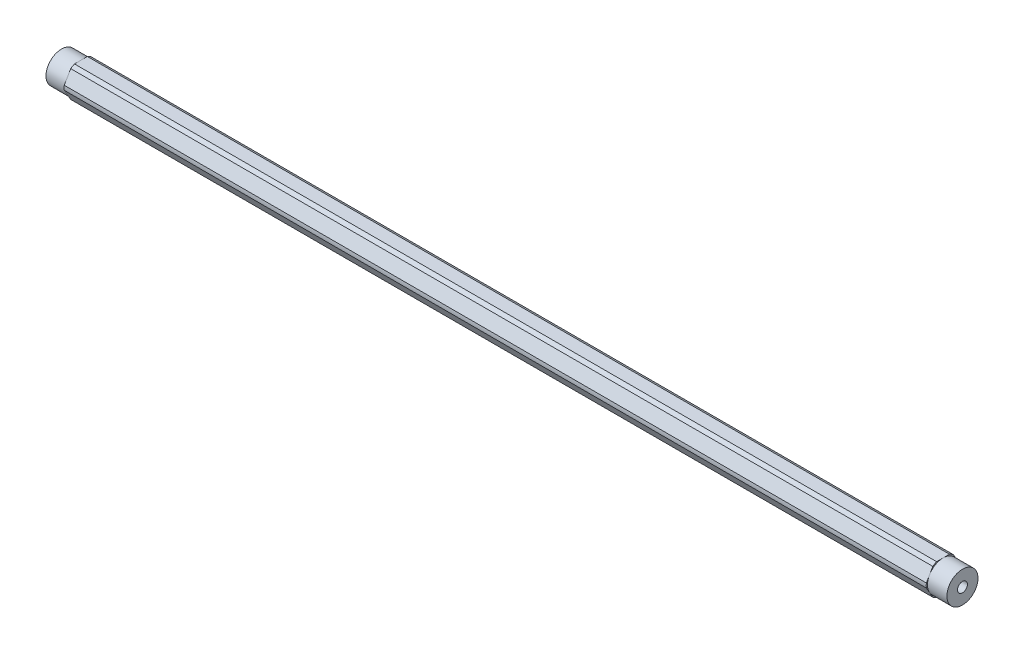
SolidWorks part; units mm, degrees
material "7075-T6 (SN)"
ref_plane "Front Plane" through (0, 0, 0) normal (0, 0, 1) x (1, 0, 0)
ref_plane "Top Plane" through (0, 0, 0) normal (0, 1, 0) x (1, 0, 0)
ref_plane "Right Plane" through (0, 0, 0) normal (1, 0, 0) x (0, 0, -1)
sketch "Sketch1" plane through (0, 0, 0) normal (1, 0, 0) x (0, 0, -1)
  line L1 (3.6662, 6.35) -> (-3.6662, 6.35)
  line L2 (-3.6662, 6.35) -> (-7.3323, 0)
  line L3 (-7.3323, 0) -> (-3.6662, -6.35)
  line L4 (-3.6662, -6.35) -> (3.6662, -6.35)
  line L5 (3.6662, -6.35) -> (7.3323, 0)
  line L6 (7.3323, 0) -> (3.6662, 6.35)
  circle A0 centre (0, 0) radius 2.0193
  circle A1 centre (0, 0) radius 6.875
  circle A2 centre (0, 0) radius 6.35 construction
  dimension "D1" = 13.75
  dimension "D2" = 4.0386
  dimension "D3" = 12.7
extrude "Boss-Extrude1" add sketch "Sketch1" along normal mid plane 368.3 contours L6 A1 L1 L2 L3 L4 L5 A0
sketch "Sketch2" plane through (184.15, 0, 0) normal (1, 0, 0) x (0, 0, -1)
  circle A0 centre (0, 0) radius 6.35
  dimension "D1" = 12.7
extrude "Cut-Extrude-Thin1" cut sketch "Sketch2" against normal blind 7.9375 thin
mirror "Mirror1" about plane through (0, 0, 0) normal (1, 0, 0) of "Cut-Extrude-Thin1"
equation "\"D1@Sketch1\"=13.75mm"
